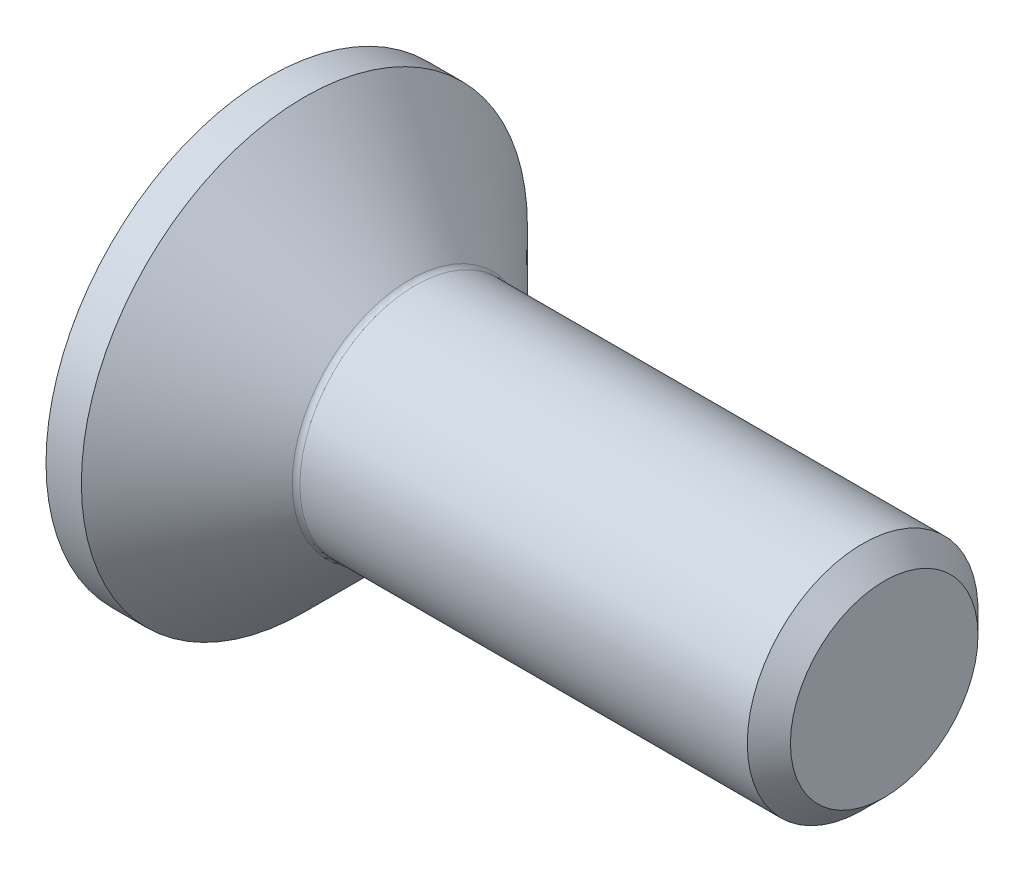
SolidWorks part; units mm, degrees
ref_plane "Plane1" through (0, 0, 0) normal (0, 0, 1) x (1, 0, 0)
ref_plane "Plane2" through (0, 0, 0) normal (0, 1, 0) x (1, 0, 0)
ref_plane "Plane3" through (0, 0, 0) normal (1, 0, 0) x (0, 0, -1)
sketch "BodySke" plane through (0, 0, 0) normal (0, 0, 1) x (1, 0, 0)
  line L0 (0, 0) -> (0, 2.9)
  line L1 (0.46, 2.9) -> (1.86, 1.5)
  line L2 (0, 2.9) -> (0.46, 2.9)
  line L3 (1.86, 1.5) -> (7.7195, 1.5)
  line L4 (8, 1.2195) -> (8, 0)
  line L5 (8, 0) -> (0, 0)
  line L6 (0, 0) -> (127, 0) construction
  line L7 (0.46, -2.9) -> (1.86, -1.5) construction
  line L8 (8, 1.2195) -> (7.7195, 1.5)
  line L9 (0, -2.9) -> (0.46, -2.9) construction
  line L10 (8, -1.2195) -> (7.7195, -1.5) construction
  line L11 (2.36, 7.85) -> (2.36, -14.375) construction
  line L12 (0, 19.05) -> (0, -3.175) construction
  dimension "D1" = 0.46
  dimension "Diameter" = 3
  dimension "Head_ht" = 1.86
  dimension "Length" = 8
  dimension "Body_ch_ang" = 45
  dimension "Head_dia" = 5.8
  dimension "Minor_dia" = 2.439
  dimension "Head_ang" = 90
  dimension "Advance" = 0.5
  dimension "Thread_nom" = 8
revolve "BaseBody" add sketch "BodySke" angle 360 about L6
cosmetic thread "ThreadCosmetic" parameters "Thread_length"=5.14, "Thread_minor"=2.439
fillet "Fillet1" radius 0.1 1 edges at (1.86, 0, 1.5)
sketch "Sketch2" plane through (0, 0, 0) normal (0, 0, 1) x (1, 0, 0)
  line L0 (0, 1) -> (1.1, 1)
  line L1 (1.1, 1) -> (1.6774, 0)
  line L2 (0, 0) -> (127, 0) construction
  line L3 (1.6774, 0) -> (0, 0)
  line L4 (0, 0) -> (0, 1)
  line L5 (0, -1) -> (1.1, -1) construction
  line L6 (0, 0) -> (47.625, 0) construction
  line L8 (0, 2.9) -> (0, -2.9) construction
  dimension "D2" = 60
  dimension "PreBroach_depth" = 1.1
  dimension "PreBroach_dia" = 2
revolve "PreBroach" cut sketch "Sketch2" angle 360 about L6
sketch "Sketch3" plane through (0, 0, 0) normal (-1, 0, 0) x (0, 0, 1)
  line L0 (-1, -0.5774) -> (-1, 0.5774)
  line L1 (-1, 0.5774) -> (0, 1.1547)
  line L2 (0, 1.1547) -> (1, 0.5774)
  line L3 (1, 0.5774) -> (1, -0.5774)
  line L4 (1, -0.5774) -> (0, -1.1547)
  line L5 (0, -1.1547) -> (-1, -0.5774)
  dimension "D1" = 1
  dimension "D2" = 1
  dimension "D3" = 2
  dimension "Hex_size" = 2
extrude "Hex" cut sketch "Sketch3" against normal blind 1.1
sketch "ThdSchSke" plane through (0, 0, 0) normal (0, 0, 1) x (1, 0, 0)
  line L0 (2.86, -1.2195) -> (2.6636, -1.5)
  line L1 (2.86, -1.2195) -> (3.0564, -1.5)
  line L2 (3.0564, -1.5) -> (3.0564, -1.875)
  line L3 (-3.175, 0) -> (5.1513, 0) construction
  line L4 (0, 2.9) -> (0, -2.9) construction
  line L5 (3.0564, -1.875) -> (2.6636, -1.875)
  line L6 (2.6636, -1.875) -> (2.6636, -1.5)
  dimension "Thread_minor" = 2.439
  dimension "Diameter" = 3
  dimension "Start" = 2.86
  dimension "SideAngle" = 55
  dimension "VeeAngle" = 70
  dimension "Overcut" = 3.75
revolve "ThreadSchematic" [suppressed] cut sketch "ThdSchSke" angle 360 about L3
pattern_linear "ThdSchPat" [suppressed]
equation "\"Thread_minor@ThreadCosmetic\"  =  \"Minor_dia@BodySke\""
equation "\"D1@Sketch3\" = \"Hex_size@Sketch3\" / 2"
equation "\"D2@Sketch3\" = \"D1@Sketch3\""
equation "\"D3@Sketch3\" = \"Hex_size@Sketch3\""
equation "\"Thread_length@ThreadCosmetic\" = ((sgn( (\"Length@BodySke\" - \"Advance@BodySke\" * 2.0 - \"Head_ht@BodySke\" ) - \"Thread_nom@BodySke\" )-1)*( (\"Length@BodySke\" - \"Advance@BodySke\" * 2.0 - \"Head_ht@BodySke\" ) - \"Thread_nom@BodySke\" ))/-2+ \"Thread_nom@BodySke\""
equation "\"Thread_minor@ThdSchSke\" = \"Minor_dia@BodySke\""
equation "\"Diameter@ThdSchSke\" = \"Diameter@BodySke\""
equation "\"Overcut@ThdSchSke\" = \"Diameter@BodySke\" * 1.25"
equation "\"Start@ThdSchSke\" = 0.000001 + \"Length@BodySke\" - \"Thread_length@ThreadCosmetic\"  '---Countersunk---"
equation "\"Num_threads@ThdSchPat\" = int( \"Thread_length@ThreadCosmetic\" / \"Advance@BodySke\" + 0.999 )  + 1"
equation "\"Advance@ThdSchPat\" = \"Thread_length@ThreadCosmetic\" /  (\"Num_threads@ThdSchPat\" - 1) 'relax it"
equation "\"Num_threads@ThdSchPat\" = \"Num_threads@ThdSchPat\" - sgn( \"Num_threads@ThdSchPat\" - 1) '---chamfered tips only---"
